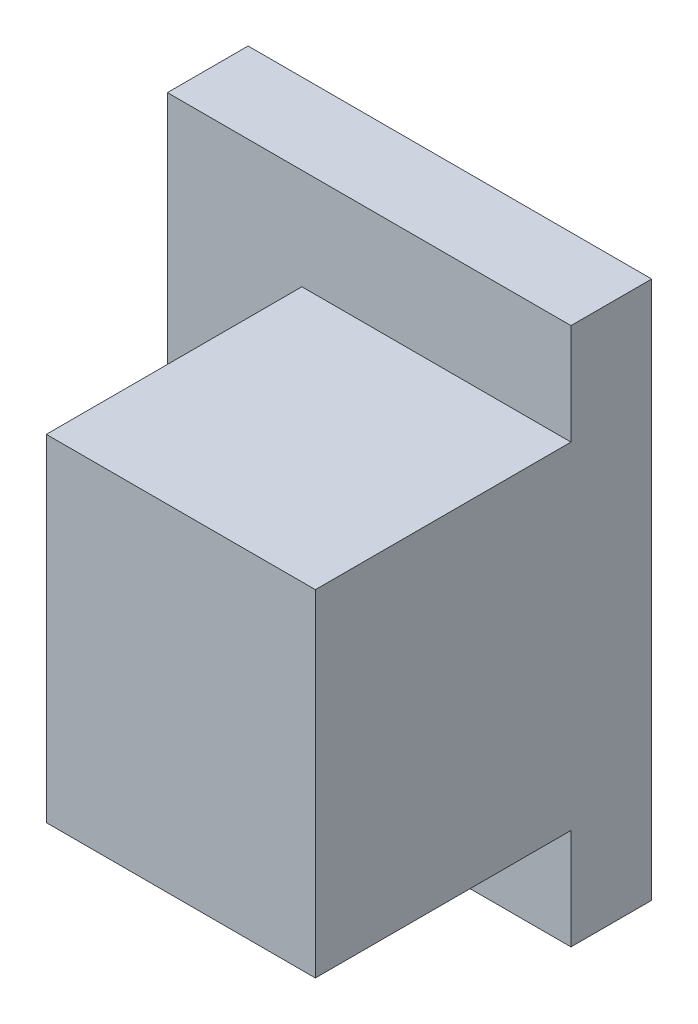
SolidWorks part; units mm, degrees
ref_plane "前视基准面" through (0, 0, 0) normal (0, 0, 1) x (1, 0, 0)
ref_plane "上视基准面" through (0, 0, 0) normal (0, 1, 0) x (1, 0, 0)
ref_plane "右视基准面" through (0, 0, 0) normal (1, 0, 0) x (0, 0, -1)
other "Configuration Table"
sketch "草图1" plane through (0, 0, 0) normal (0, 0, 1) x (1, 0, 0)
  line L1 (0, 0) -> (2, 0)
  line L2 (0, 0) -> (0, 3)
  line L3 (0, 3) -> (2, 3)
  line L4 (2, 0) -> (2, 3)
  line L5 (-1, 4) -> (3, 4)
  line L6 (-1, 4) -> (-1, -1)
  line L7 (-1, -1) -> (3, -1)
  line L8 (3, 4) -> (3, -1)
  dimension "D1" = 2
  dimension "D2" = 3
  dimension "D3" = 1
  dimension "D4" = 1
  dimension "D5" = 1
  dimension "D6" = 1
extrude "凸台-拉伸1" add sketch "草图1" along normal blind 4
sketch "草图2" plane through (0, 0, 0) normal (0, 0, -1) x (-1, 0, 0)
  line L0 (-3, 4) -> (1, 4)
  line L1 (1, 4) -> (1, -1)
  line L2 (1, -1) -> (-3, -1)
  line L3 (-3, -1) -> (-3, -2.5)
  line L4 (-3, -2.5) -> (3, -2.5)
  line L5 (3, -2.5) -> (3, 5.5)
  line L6 (3, 5.5) -> (-3, 5.5)
  line L7 (-3, 5.5) -> (-3, 4)
  dimension "D1" = 1.5
  dimension "D2" = 2
  dimension "D3" = 1.5
extrude "凸台-拉伸2" add sketch "草图2" against normal blind 1.2
sketch "草图3" plane through (0, 0, 4) normal (0, 0, 1) x (1, 0, 0)
  line L4 (-1, 4) -> (-1, -1)
  line L5 (-1, -1) -> (3, -1)
  line L6 (3, -1) -> (3, 4)
  line L7 (3, 4) -> (-1, 4)
  line L8 (-1, 4) -> (-1, -1)
  line L9 (-1, -1) -> (3, -1)
  line L10 (3, -1) -> (3, 4)
  line L11 (3, 4) -> (-1, 4)
  dimension "D1" = 0
extrude "凸台-拉伸3" add sketch "草图3" along normal blind 1
